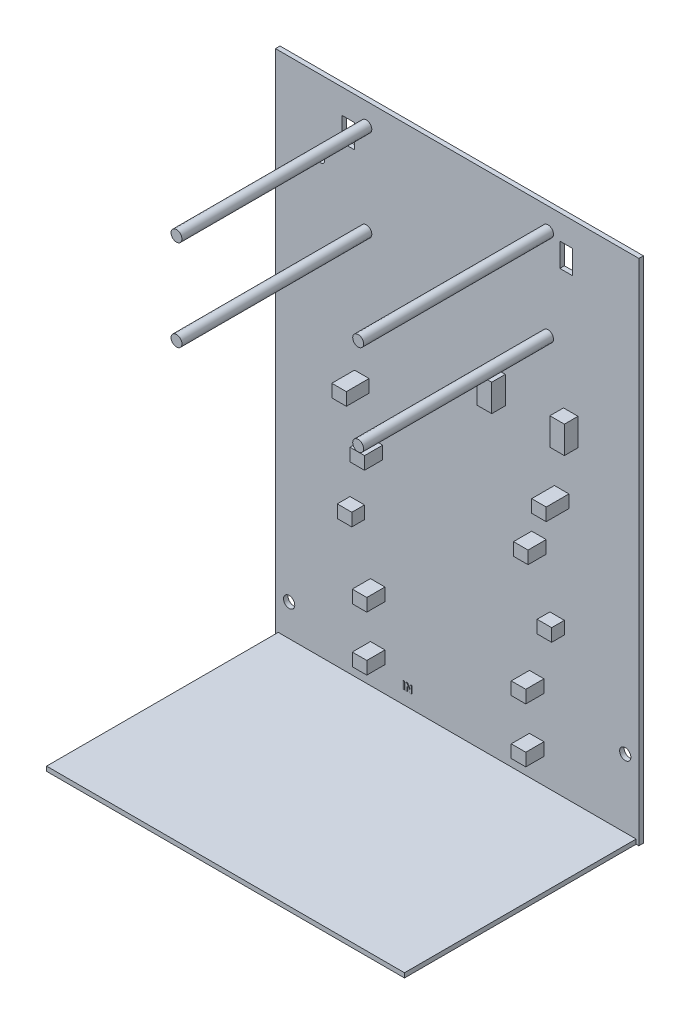
SolidWorks part; units mm, degrees
ref_plane "Front Plane" through (0, 0, 0) normal (0, 0, 1) x (1, 0, 0)
ref_plane "Top Plane" through (0, 0, 0) normal (0, 1, 0) x (1, 0, 0)
ref_plane "Right Plane" through (0, 0, 0) normal (1, 0, 0) x (0, 0, -1)
other "Configuration Table"
sketch "Sketch1" plane through (0, 0, 0) normal (0, 0, 1) x (1, 0, 0)
  line L0 (-200, 0) -> (200, 0)
  line L1 (200, 0) -> (200, 560)
  line L2 (200, 560) -> (-200, 560)
  line L3 (-200, 560) -> (-200, 0)
extrude "Panel" add sketch "Sketch1" along normal blind 5
sketch "Sketch2" plane through (0, 0, 0) normal (0, 1, 0) x (1, 0, 0)
  line L0 (-197, -260) -> (197, -260)
  line L1 (197, -260) -> (197, -5)
  line L2 (197, -5) -> (-197, -5)
  line L3 (-197, -5) -> (-197, -260)
extrude "Shelf" add sketch "Sketch2" along normal blind 5
sketch "Sketch3" plane through (0, 0, 0) normal (0, 0, 1) x (1, 0, 0)
  line L0 (-127, 507) -> (-113, 507)
  line L1 (-113, 507) -> (-113, 533)
  line L2 (-113, 533) -> (-127, 533)
  line L3 (-127, 533) -> (-127, 507)
  line L4 (113, 507) -> (127, 507)
  line L5 (127, 507) -> (127, 533)
  line L6 (127, 533) -> (113, 533)
  line L7 (113, 533) -> (113, 507)
extrude "Wall_Keyholes" cut sketch "Sketch3" along normal through all and the other way through all
sketch "Sketch4" plane through (0, 0, 0) normal (0, 0, 1) x (1, 0, 0)
  circle A0 centre (-185, 40) radius 6.2
  circle A1 centre (185, 80) radius 6.2
  circle A2 centre (-150, 480) radius 4.1
  dimension "D1" = 12.4
  dimension "D2" = 12.4
  dimension "D3" = 8.2
extrude "Connector_Holes" cut sketch "Sketch4" along normal through all and the other way through all
sketch "Sketch5" plane through (0, 0, 0) normal (0, 0, 1) x (1, 0, 0)
  circle A0 centre (-100, 436) radius 6
  circle A1 centre (-100, 536) radius 6
  circle A2 centre (100, 436) radius 6
  circle A3 centre (100, 536) radius 6
  dimension "D1" = 12
  dimension "D2" = 12
  dimension "D3" = 12
  dimension "D4" = 12
extrude "Module_Posts" add sketch "Sketch5" along normal blind 209 from offset 5
sketch "Sketch6" plane through (0, 0, 0) normal (0, 0, 1) x (1, 0, 0)
  line L0 (-95.5, 33) -> (-79.5, 33)
  line L1 (-79.5, 33) -> (-79.5, 47)
  line L2 (-79.5, 47) -> (-95.5, 47)
  line L3 (-95.5, 47) -> (-95.5, 33)
  line L4 (79.5, 33) -> (95.5, 33)
  line L5 (95.5, 33) -> (95.5, 47)
  line L6 (95.5, 47) -> (79.5, 47)
  line L7 (79.5, 47) -> (79.5, 33)
extrude "Saddles_SED" add sketch "Sketch6" along normal blind 20 from offset 5
sketch "Sketch7" plane through (0, 0, 0) normal (0, 0, 1) x (1, 0, 0)
  line L0 (-95.5, 93) -> (-79.5, 93)
  line L1 (-79.5, 93) -> (-79.5, 107)
  line L2 (-79.5, 107) -> (-95.5, 107)
  line L3 (-95.5, 107) -> (-95.5, 93)
  line L4 (79.5, 93) -> (95.5, 93)
  line L5 (95.5, 93) -> (95.5, 107)
  line L6 (95.5, 107) -> (79.5, 107)
  line L7 (79.5, 107) -> (79.5, 93)
extrude "Saddles_CARB" add sketch "Sketch7" along normal blind 20 from offset 5
sketch "Sketch8" plane through (0, 0, 0) normal (0, 0, 1) x (1, 0, 0)
  line L0 (-118, 160) -> (-102, 160)
  line L1 (-102, 160) -> (-102, 174)
  line L2 (-102, 174) -> (-118, 174)
  line L3 (-118, 174) -> (-118, 160)
  line L4 (102, 160) -> (118, 160)
  line L5 (118, 160) -> (118, 174)
  line L6 (118, 174) -> (102, 174)
  line L7 (102, 174) -> (102, 160)
extrude "Saddles_RO" add sketch "Sketch8" along normal blind 14 from offset 5
sketch "Sketch9" plane through (0, 0, 0) normal (0, 0, 1) x (1, 0, 0)
  line L0 (-98, 227) -> (-82, 227)
  line L1 (-82, 227) -> (-82, 241)
  line L2 (-82, 241) -> (-98, 241)
  line L3 (-98, 241) -> (-98, 227)
  line L4 (82, 227) -> (98, 227)
  line L5 (98, 227) -> (98, 241)
  line L6 (98, 241) -> (82, 241)
  line L7 (82, 241) -> (82, 227)
extrude "Saddles_UF" add sketch "Sketch9" along normal blind 20 from offset 5
sketch "Sketch10" plane through (0, 0, 0) normal (0, 0, 1) x (1, 0, 0)
  line L0 (-113, 283) -> (-97, 283)
  line L1 (-97, 283) -> (-97, 297)
  line L2 (-97, 297) -> (-113, 297)
  line L3 (-113, 297) -> (-113, 283)
  line L4 (107, 283) -> (123, 283)
  line L5 (123, 283) -> (123, 297)
  line L6 (123, 297) -> (107, 297)
  line L7 (107, 297) -> (107, 283)
extrude "Saddles_UVC" add sketch "Sketch10" along normal blind 25 from offset 5
sketch "Sketch11" plane through (0, 0, 0) normal (0, 0, 1) x (1, 0, 0)
  line L0 (37, 346) -> (53, 346)
  line L1 (53, 346) -> (53, 376)
  line L2 (53, 376) -> (37, 376)
  line L3 (37, 376) -> (37, 346)
  line L4 (117, 346) -> (133, 346)
  line L5 (133, 346) -> (133, 376)
  line L6 (133, 376) -> (117, 376)
  line L7 (117, 376) -> (117, 346)
extrude "Pump_Mount_Posts" add sketch "Sketch11" along normal blind 15 from offset 5
sketch "Sketch12" plane through (0, 0, 0) normal (0, 0, 1) x (1, 0, 0)
  text T0 "IN" font "Arial" height 8
extrude "Label_IN" add sketch "Sketch12" along normal blind 0.6 from offset 5
equation "\"Jar_OD\"= 90  'ASSUMED - Part G fallback - jar outer diameter"
equation "\"Jar_H\"= 120  'ASSUMED - Part G fallback - jar height"
equation "\"Pump_L\"= 45  'ASSUMED - Part G fallback"
equation "\"Pump_W\"= 24  'ASSUMED - Part G fallback"
equation "\"Pump_H\"= 33  'ASSUMED - Part G fallback"
equation "\"Pump_Outlet_OD\"= 7.5  'ASSUMED - Part G fallback"
equation "\"Tube_OD\"= 8  'ASSUMED - Part G fallback"
equation "\"Tube_ID\"= 6  'ASSUMED - Part G fallback"
equation "\"TDS_Body_Dia\"= 12  'ASSUMED - Part G fallback"
equation "\"TDS_Wet_Len\"= 45  'ASSUMED - Part G fallback - length in water"
equation "\"DS_Tube_Dia\"= 6  'ASSUMED - Part G fallback"
equation "\"DS_Tube_Len\"= 50  'ASSUMED - Part G fallback"
equation "\"ORP_Body_Dia\"= 12  'ASSUMED - Part G fallback"
equation "\"ORP_Body_Len\"= 150  'ASSUMED - Part G fallback"
equation "\"ORP_Cap_Dia\"= 16  'ASSUMED - Part G fallback"
equation "\"Turb_W\"= 33  'ASSUMED - Part G fallback - head width"
equation "\"Turb_D\"= 28  'ASSUMED - Part G fallback - head depth"
equation "\"Turb_H\"= 30  'ASSUMED - Part G fallback - head height"
equation "\"Turb_Slot_W\"= 10  'ASSUMED - Part G fallback - slot width"
equation "\"Flow_L\"= 62  'ASSUMED - Part G fallback YF-S201"
equation "\"Flow_W\"= 36  'ASSUMED - Part G fallback"
equation "\"Flow_H\"= 35  'ASSUMED - Part G fallback"
equation "\"Thread_G12_OD\"= 20.955  'ASSUMED - Part G fallback thread G1/2 (major diameter)"
equation "\"Valve_L\"= 75  'ASSUMED - Part G fallback"
equation "\"Valve_W\"= 45  'ASSUMED - Part G fallback"
equation "\"Valve_H\"= 60  'ASSUMED - Part G fallback"
equation "\"Tee_L\"= 40  'ASSUMED - Part G fallback - overall length"
equation "\"Tee_Branch_L\"= 25  'ASSUMED - Part G fallback"
equation "\"Tee_OD\"= 12  'ASSUMED - Part G fallback"
equation "\"LED_Board_L\"= 20  'ASSUMED - Part G fallback"
equation "\"LED_Board_W\"= 20  'ASSUMED - Part G fallback - LED at centre"
equation "\"GUVA_L\"= 20  'ASSUMED - Part G fallback"
equation "\"GUVA_W\"= 12  'ASSUMED - Part G fallback - sensor at centre"
equation "\"Reed_L\"= 27  'ASSUMED - Part G fallback MC-38 half"
equation "\"Reed_W\"= 14  'ASSUMED - Part G fallback"
equation "\"Reed_H\"= 8  'ASSUMED - Part G fallback"
equation "\"ESP_L\"= 51  'ASSUMED - Part G fallback"
equation "\"ESP_W\"= 28  'ASSUMED - Part G fallback"
equation "\"TFT_L\"= 58  'ASSUMED - Part G fallback - board"
equation "\"TFT_W\"= 35  'ASSUMED - Part G fallback - board"
equation "\"TFT_Win_L\"= 35  'ASSUMED - Part G fallback - visible window"
equation "\"TFT_Win_W\"= 28  'ASSUMED - Part G fallback - visible window"
equation "\"Relay_L\"= 50  'ASSUMED - Part G fallback"
equation "\"Relay_W\"= 26  'ASSUMED - Part G fallback"
equation "\"Relay_H\"= 19  'ASSUMED - Part G fallback"
equation "\"Mosfet_L\"= 34  'ASSUMED - Part G fallback"
equation "\"Mosfet_W\"= 17  'ASSUMED - Part G fallback"
equation "\"Mosfet_H\"= 12  'ASSUMED - Part G fallback"
equation "\"TDS_Board_L\"= 42  'ASSUMED - Part G fallback"
equation "\"TDS_Board_W\"= 32  'ASSUMED - Part G fallback"
equation "\"Turb_Board_L\"= 38  'ASSUMED - Part G fallback"
equation "\"Turb_Board_W\"= 28  'ASSUMED - Part G fallback"
equation "\"BNC_Thread_Dia\"= 9.5  'ASSUMED - Part G fallback"
equation "\"Plate_L\"= 420  'ASSUMED - Part G fallback"
equation "\"Plate_W\"= 297  'ASSUMED - Part G fallback"
equation "\"Plate_T\"= 6  'ASSUMED - Part G fallback"
equation "\"Booster_L\"= 150  'ASSUMED - Part G fallback - booster pump"
equation "\"Booster_W\"= 95  'ASSUMED - Part G fallback"
equation "\"Booster_H\"= 100  'ASSUMED - Part G fallback"
equation "\"PTube_OD\"= 6.35  'ASSUMED - Part G fallback - product tube 1/4 inch"
equation "\"Qz_Out\"= 12  'ASSUMED - Part G fallback - quartz channel outside square"
equation "\"Qz_Path\"= 10  'ASSUMED - Part G fallback - quartz channel inside light path"
equation "\"Qz_L\"= 40  'ASSUMED - Part G fallback - quartz channel length"
equation "\"LED860_Dia\"= 5  'ASSUMED - Part G fallback - 860 nm LED"
equation "\"BPW_L\"= 5.4  'ASSUMED - Part G fallback - BPW34"
equation "\"BPW_W\"= 4.3  'ASSUMED - Part G fallback - BPW34"
equation "\"Cart_Dia\"= 50  'ASSUMED - Part G fallback - sediment and pre-carbon cartridges"
equation "\"Cart_L\"= 255  'ASSUMED - Part G fallback"
equation "\"UF_Dia\"= 50  'ASSUMED - Part G fallback - UF cartridge"
equation "\"UF_L\"= 260  'ASSUMED - Part G fallback"
equation "\"RO_Dia\"= 62  'ASSUMED - Part G fallback - RO membrane housing"
equation "\"RO_L\"= 300  'ASSUMED - Part G fallback"
equation "\"UVC_Dia\"= 40  'ASSUMED - Part G fallback - UV-C chamber"
equation "\"UVC_L\"= 300  'ASSUMED - Part G fallback"
equation "\"Tank_W\"= 260  'ASSUMED - Part G fallback - storage tank"
equation "\"Tank_D\"= 160  'ASSUMED - Part G fallback"
equation "\"Tank_H\"= 300  'ASSUMED - Part G fallback"
equation "\"Cab_W\"= 400  'ASSUMED - Part G fallback - purifier cabinet"
equation "\"Cab_D\"= 270  'ASSUMED - Part G fallback"
equation "\"Cab_H\"= 560  'ASSUMED - Part G fallback"
equation "\"ORP_Board_L\"= 40  'ASSUMED - Part G fallback - ORP buffer board"
equation "\"ORP_Board_W\"= 30  'ASSUMED - Part G fallback"
equation "\"Opt_Board_L\"= 50  'ASSUMED - Part G fallback - optical front-end board"
equation "\"Opt_Board_W\"= 40  'ASSUMED - Part G fallback"
equation "\"Buck_L\"= 43  'ASSUMED - Part G fallback - 12 V to 5 V buck module"
equation "\"Buck_W\"= 21  'ASSUMED - Part G fallback"
equation "\"Buck_H\"= 14  'ASSUMED - Part G fallback"
equation "\"BB_L\"= 165  'ASSUMED - Part G fallback - breadboard (As_Built_R3 only)"
equation "\"BB_W\"= 55  'ASSUMED - Part G fallback"
equation "\"BB_H\"= 10  'ASSUMED - Part G fallback"
equation "\"Cuv_W\"= 12.5  'ASSUMED - old R3 cuvette (station suppressed in SS4)"
equation "\"Cuv_D\"= 12.5  'ASSUMED - old R3 cuvette (station suppressed in SS4)"
equation "\"Cuv_H\"= 45  'ASSUMED - old R3 cuvette (station suppressed in SS4)"
equation "\"Probe_Clr\"= 0.3  'DESIGN VALUE - Part C rule 3 - printed probe hole = diameter + 0.3"
equation "\"Label_H\"= 0.6  'DESIGN VALUE - Part D - raised label height"
equation "\"D1@Label_IN\" = \"Label_H\""
